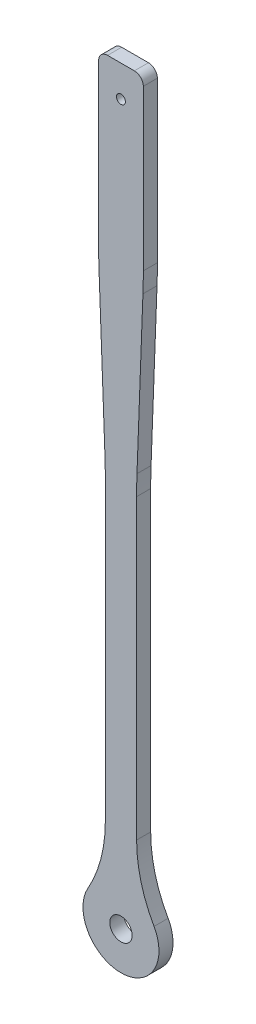
SolidWorks part; units mm, degrees
material "Hexcel AS4C (3000 Filaments)"
ref_plane "Front Plane" through (0, 0, 0) normal (0, 0, 1) x (1, 0, 0)
ref_plane "Top Plane" through (0, 0, 0) normal (0, 1, 0) x (1, 0, 0)
ref_plane "Right Plane" through (0, 0, 0) normal (1, 0, 0) x (0, 0, -1)
sketch "Sketch2" plane through (0, 0, 0) normal (0, 0, 1) x (1, 0, 0)
  line L0 (4.552, 53.6545) -> (6.243, 98.7455)
  line L1 (-4.445, -50.8) -> (4.445, -50.8) construction
  line L2 (-4.445, -36.5408) -> (-4.445, 47.9435)
  line L3 (-4.445, 50.8) -> (4.445, 50.8) construction
  line L4 (4.445, -36.5408) -> (4.445, 47.9435)
  line L5 (-4.445, -50.8) -> (4.445, 50.8) construction
  line L6 (-4.445, 50.8) -> (4.445, -50.8) construction
  line L7 (6.35, 104.4565) -> (6.35, 149.86)
  line L8 (3.81, 152.4) -> (-3.81, 152.4)
  line L9 (-6.35, 149.86) -> (-6.35, 104.4565)
  line L10 (-6.243, 98.7455) -> (-4.552, 53.6545)
  circle A0 centre (0, 143.51) radius 1.27
  arc A1 (-9.3931, -55.3174) -> (9.3931, -55.3174) centre (0, -60.6374) ccw
  circle A2 centre (0, -60.6374) radius 3.175
  arc A3 (9.3931, -55.3174) -> (4.445, -36.5408) centre (42.545, -36.5408) cw
  arc A4 (-9.3931, -55.3174) -> (-4.445, -36.5408) centre (-42.545, -36.5408) ccw
  arc A5 (6.35, 149.86) -> (3.81, 152.4) centre (3.81, 149.86) ccw
  arc A6 (-3.81, 152.4) -> (-6.35, 149.86) centre (-3.81, 149.86) ccw
  arc A7 (6.243, 98.7455) -> (6.35, 104.4565) centre (-146.05, 104.4565) ccw
  arc A8 (-6.35, 104.4565) -> (-6.243, 98.7455) centre (146.05, 104.4565) ccw
  arc A9 (-4.445, 47.9435) -> (-4.552, 53.6545) centre (-156.845, 47.9435) ccw
  arc A10 (4.552, 53.6545) -> (4.445, 47.9435) centre (156.845, 47.9435) ccw
  point P0 (0, 0)
  point P14 (0, 152.4)
  point P23 (6.35, 152.4)
  point P26 (-6.35, 152.4)
  point P29 (6.35, 101.6)
  point P32 (-6.35, 101.6)
  dimension "D3" = 2.54
  dimension "D8" = 6.35
  dimension "D9" = 7.62
  dimension "D10" = 38.1
  dimension "D11" = 2.54
  dimension "D12" = 152.4
  dimension "D1" = 8.89
  dimension "D2" = 101.6
  dimension "D4" = 50.8
  dimension "D5" = 50.8
  dimension "D6" = 12.7
  dimension "D7" = 8.89
extrude "Boss-Extrude1" add sketch "Sketch2" along normal blind 4
